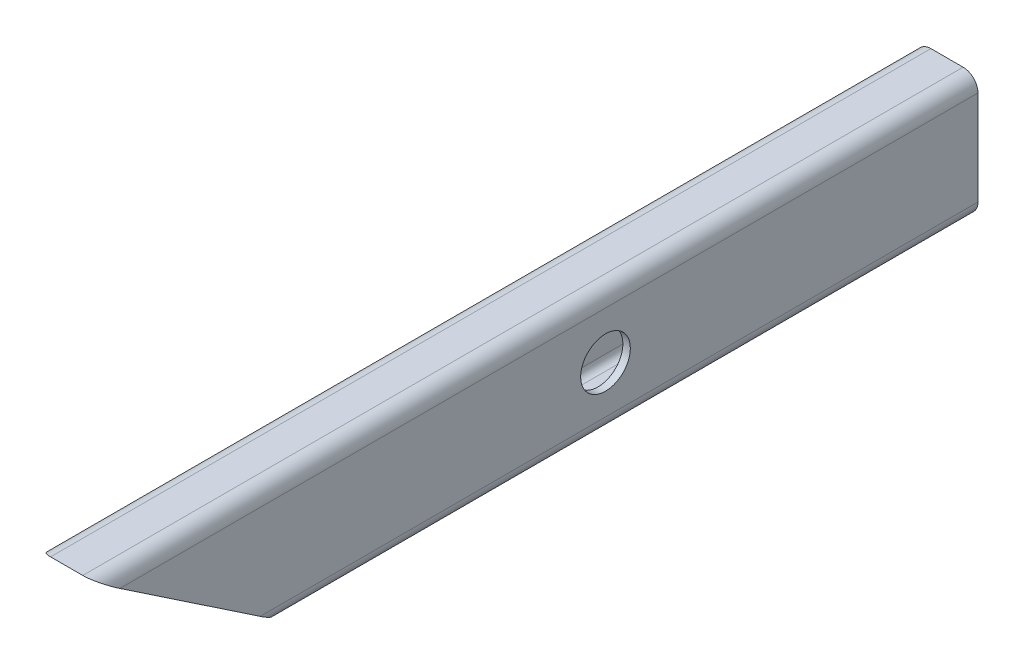
SolidWorks part; units mm, degrees
material "AISI 1020 Steel, Cold Rolled"
ref_plane "Front Plane" through (0, 0, 0) normal (0, 0, 1) x (1, 0, 0)
ref_plane "Top Plane" through (0, 0, 0) normal (0, 1, 0) x (1, 0, 0)
ref_plane "Right Plane" through (0, 0, 0) normal (1, 0, 0) x (0, 0, -1)
sketch "Sketch1" plane through (0, 0, 0) normal (0, 0, 1) x (1, 0, 0)
  line L4 (0, 44) -> (0, 6)
  line L10 (3, 44) -> (3, 6)
  line L11 (6, 47) -> (18.9612, 47)
  line L12 (21.9612, 44) -> (21.9612, 6)
  line L13 (24.9612, 44) -> (24.9612, 6)
  line L14 (6, 50) -> (18.9612, 50)
  line L15 (6, 3) -> (18.9612, 3)
  line L16 (6, 0) -> (18.9612, 0)
  arc A0 (6, 3) -> (3, 6) centre (6, 6) cw
  arc A1 (6, 0) -> (0, 6) centre (6, 6) cw
  arc A2 (18.9612, 3) -> (21.9612, 6) centre (18.9612, 6) ccw
  arc A3 (18.9612, 0) -> (24.9612, 6) centre (18.9612, 6) ccw
  arc A4 (6, 47) -> (3, 44) centre (6, 44) ccw
  arc A5 (6, 50) -> (0, 44) centre (6, 44) ccw
  arc A6 (18.9612, 47) -> (21.9612, 44) centre (18.9612, 44) cw
  arc A7 (18.9612, 50) -> (24.9612, 44) centre (18.9612, 44) cw
extrude "Boss-Extrude1" add sketch "Sketch1" along normal blind 356.5
sketch "Sketch2" plane through (24.9612, 0, 0) normal (1, 0, 0) x (0, 0, -1)
  line L0 (0, 25) -> (0, 50)
  line L1 (0, 6) -> (0, 44) construction
  line L3 (-356.5, 50) -> (-356.5, 0)
  line L4 (0, 0) -> (-291.6, 0)
  line L5 (-356.5, 0) -> (0, 0) construction
  line L6 (-356.5, 50) -> (-354.5, 50)
  line L7 (-356.5, 0) -> (-291.6, 0)
  line L8 (-354.5, 50) -> (-280.1145, 0)
extrude "Cut-Extrude1" cut sketch "Sketch2" against normal through all
sketch "Sketch3" plane through (24.9612, 0, 0) normal (1, 0, 0) x (0, 0, -1)
  line L0 (0, 25) -> (-150, 25)
  line L1 (0, 6) -> (0, 44) construction
  circle A0 centre (-150, 25) radius 10
extrude "Cut-Extrude2" cut sketch "Sketch3" against normal through all
